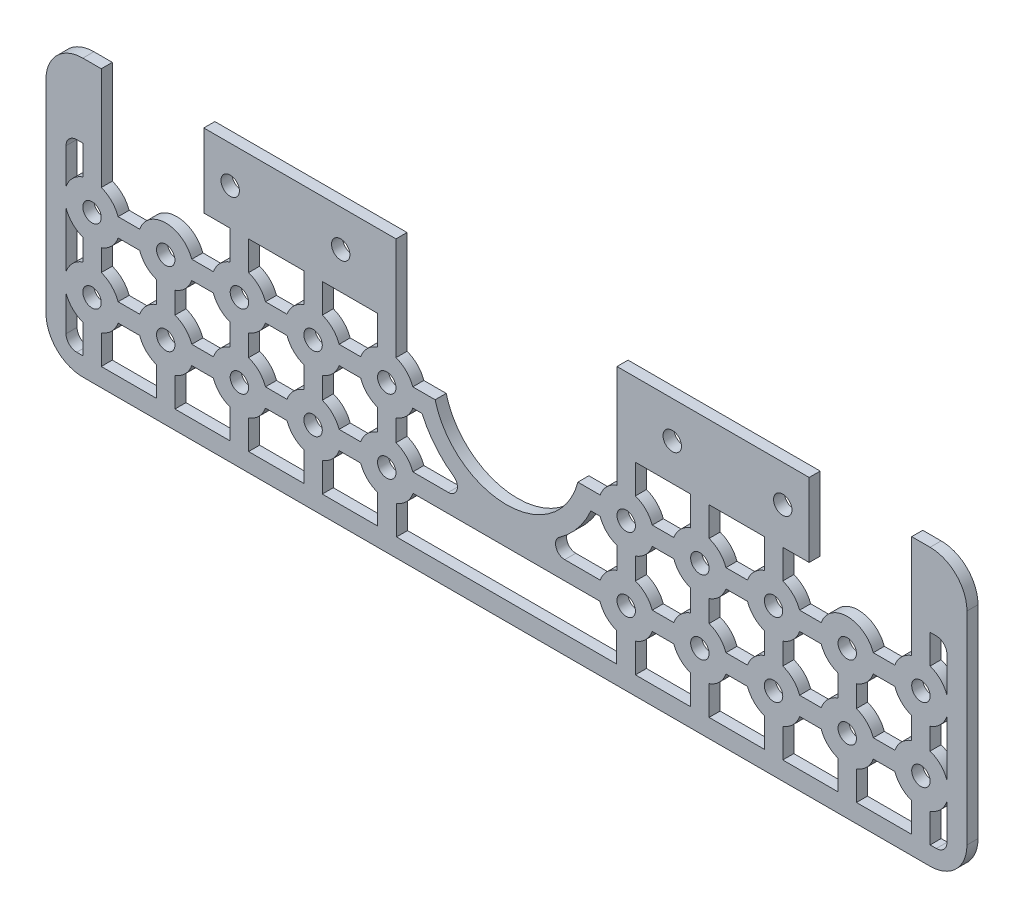
SolidWorks part; units mm, degrees
ref_plane "Front Plane" through (0, 0, 0) normal (0, 0, 1) x (1, 0, 0)
ref_plane "Top Plane" through (0, 0, 0) normal (0, 1, 0) x (1, 0, 0)
ref_plane "Right Plane" through (0, 0, 0) normal (1, 0, 0) x (0, 0, -1)
sketch "Sketch1" plane through (0, 0, 0) normal (0, 0, 1) x (1, 0, 0)
  line L0 (-40, 20) -> (-40, 55) construction
  line L4 (-250, -55) -> (-250, 55)
  line L5 (-239.1421, 10) -> (-239.1421, 29.2093)
  line L6 (-233.3514, 35) -> (-230, 35)
  line L8 (-60, 75) -> (-230, 75) construction
  line L17 (0, -20) -> (0, -40)
  line L21 (-239.1421, 0) -> (-239.1421, -30)
  line L25 (0, -65) -> (0, -75)
  line L26 (0, 75) -> (0, -75) construction
  line L27 (-50, 95) -> (50, 95) construction
  line L32 (-239.1421, -40) -> (-239.1421, -59.1675)
  line L34 (0, -75) -> (-230, -75)
  line L35 (-59.6991, -49.1887) -> (-59.6991, -65)
  line L77 (-230, 19.1421) -> (-230, 35)
  line L78 (-220, 19.1421) -> (-220, 35) construction
  line L79 (-230, -9.1421) -> (-230, -20.8579)
  line L80 (-220, -9.1421) -> (-220, -20.8579)
  line L81 (-220, -49.1421) -> (-220, -65)
  line L82 (-230, -49.1421) -> (-230, -64.9582)
  line L85 (-199.1421, 10) -> (-210.8579, 10)
  line L86 (-199.1421, 0) -> (-210.8579, 0)
  line L87 (-190, 19.1421) -> (-190, 35) construction
  line L88 (-180, 19.1421) -> (-180, 35) construction
  line L89 (-190, -9.1421) -> (-190, -20.8579)
  line L90 (-180, -9.1421) -> (-180, -20.8579)
  line L91 (-180, -49.1421) -> (-180, -65)
  line L92 (-190, -49.1421) -> (-190, -65)
  line L93 (-199.1421, -30) -> (-210.8579, -30)
  line L94 (-199.1421, -40) -> (-210.8579, -40)
  line L95 (-159.1421, 10) -> (-170.8579, 10)
  line L96 (-159.1421, 0) -> (-170.8579, 0)
  line L97 (-150, 19.1421) -> (-150, 35)
  line L98 (-140, 19.1421) -> (-140, 35)
  line L99 (-150, -9.1421) -> (-150, -20.8579)
  line L100 (-140, -9.1421) -> (-140, -20.8579)
  line L101 (-140, -49.1421) -> (-140, -65)
  line L102 (-150, -49.1421) -> (-150, -65)
  line L103 (-159.1421, -30) -> (-170.8579, -30)
  line L104 (-159.1421, -40) -> (-170.8579, -40)
  line L105 (-119.1421, 10) -> (-130.8579, 10)
  line L106 (-119.1421, 0) -> (-130.8579, 0)
  line L107 (-110, 19.1421) -> (-110, 35)
  line L108 (-100, 19.1421) -> (-100, 35)
  line L109 (-110, -9.1421) -> (-110, -20.8579)
  line L110 (-100, -9.1421) -> (-100, -20.8579)
  line L111 (-100, -49.1421) -> (-100, -65)
  line L112 (-110, -49.1421) -> (-110, -65)
  line L113 (-119.1421, -30) -> (-130.8579, -30)
  line L114 (-119.1421, -40) -> (-130.8579, -40)
  line L115 (-79.1421, 10) -> (-90.8579, 10)
  line L116 (-79.1421, 0) -> (-90.8579, 0)
  line L117 (-70, 19.1421) -> (-70, 35)
  line L118 (-59.6991, -65) -> (0, -65)
  line L119 (-70, -9.1421) -> (-70, -20.8579)
  line L122 (-70, -49.1421) -> (-70, -65)
  line L123 (-79.1421, -30) -> (-90.8579, -30)
  line L124 (-79.1421, -40) -> (-90.8579, -40)
  line L133 (-220, -65) -> (-190, -65)
  line L134 (-220, 35) -> (-190, 35) construction
  line L135 (-180, -65) -> (-150, -65)
  line L136 (-180, 35) -> (-150, 35) construction
  line L137 (-140, -65) -> (-110, -65)
  line L138 (-140, 35) -> (-110, 35)
  line L139 (-100, -65) -> (-70, -65)
  line L140 (-100, 35) -> (-70, 35)
  line L141 (0, -40) -> (-50.7025, -40)
  line L142 (-60, 19.1421) -> (-60, 35)
  line L143 (-60, -9.1421) -> (-60, -20.8579)
  line L147 (-50.8579, -30) -> (-31.6228, -30)
  line L149 (-50.8579, 0) -> (-45.8258, 0)
  line L150 (-50.8579, 10) -> (-48.9898, 10)
  line L154 (-233.3514, -64.9582) -> (-230, -64.9582)
  line L156 (-60, 75) -> (-230, 75) construction
  line L157 (-60, 75) -> (-60, 35)
  line L159 (-48.9898, 10) -> (-38.7298, 10)
  line L160 (-164.3309, 75) -> (-164.3309, 35)
  line L162 (-180, 35) -> (-190, 35) construction
  line L165 (-164.3309, 75) -> (-60, 75)
  line L167 (-230, 75) -> (-220, 75)
  line L169 (-164.3309, 35) -> (-150, 35)
  line L170 (-220, 19.1421) -> (-220, 75)
  arc A0 (-40, 20) -> (0, -20) centre (0, 20) ccw construction
  circle A1 centre (0, 20) radius 30 construction
  arc A4 (-230, -75) -> (-250, -55) centre (-230, -55) cw
  arc A5 (-250, 55) -> (-230, 75) centre (-230, 55) cw
  arc A7 (-40, 55) -> (-60, 75) centre (-60, 55) ccw construction
  arc A15 (-59.6991, -49.1887) -> (-50.7025, -40) centre (-65, -35) ccw
  arc A16 (-50.8579, 10) -> (-60, 19.1421) centre (-65, 5) ccw
  arc A17 (-60, -9.1421) -> (-50.8579, 0) centre (-65, 5) ccw
  arc A22 (-60, -20.8579) -> (-50.8579, -30) centre (-65, -35) cw
  arc A23 (-28.748, -20.9091) -> (-45.8258, 0) centre (0, 20) cw
  circle A26 centre (-150, 55) radius 5
  circle A27 centre (-90, 55) radius 5
  arc A43 (-31.6228, -30) -> (-28.748, -20.9091) centre (-31.6228, -25) ccw
  arc A64 (-230, 19.1421) -> (-239.1421, 10) centre (-225, 5) ccw
  arc A65 (-210.8579, 10) -> (-220, 19.1421) centre (-225, 5) ccw
  arc A66 (-220, -9.1421) -> (-210.8579, 0) centre (-225, 5) ccw
  arc A67 (-239.1421, 0) -> (-230, -9.1421) centre (-225, 5) ccw
  arc A68 (-220, -20.8579) -> (-210.8579, -30) centre (-225, -35) cw
  arc A69 (-210.8579, -40) -> (-220, -49.1421) centre (-225, -35) cw
  arc A70 (-230, -49.1421) -> (-239.1421, -40) centre (-225, -35) cw
  arc A71 (-239.1421, -30) -> (-230, -20.8579) centre (-225, -35) cw
  arc A72 (-190, 19.1421) -> (-199.1421, 10) centre (-185, 5) ccw
  arc A73 (-170.8579, 10) -> (-180, 19.1421) centre (-185, 5) ccw
  arc A74 (-180, -9.1421) -> (-170.8579, 0) centre (-185, 5) ccw
  arc A75 (-199.1421, 0) -> (-190, -9.1421) centre (-185, 5) ccw
  arc A76 (-180, -20.8579) -> (-170.8579, -30) centre (-185, -35) cw
  arc A77 (-170.8579, -40) -> (-180, -49.1421) centre (-185, -35) cw
  arc A78 (-190, -49.1421) -> (-199.1421, -40) centre (-185, -35) cw
  arc A79 (-199.1421, -30) -> (-190, -20.8579) centre (-185, -35) cw
  arc A80 (-150, 19.1421) -> (-159.1421, 10) centre (-145, 5) ccw
  arc A81 (-130.8579, 10) -> (-140, 19.1421) centre (-145, 5) ccw
  arc A82 (-140, -9.1421) -> (-130.8579, 0) centre (-145, 5) ccw
  arc A83 (-159.1421, 0) -> (-150, -9.1421) centre (-145, 5) ccw
  arc A84 (-140, -20.8579) -> (-130.8579, -30) centre (-145, -35) cw
  arc A85 (-130.8579, -40) -> (-140, -49.1421) centre (-145, -35) cw
  arc A86 (-150, -49.1421) -> (-159.1421, -40) centre (-145, -35) cw
  arc A87 (-159.1421, -30) -> (-150, -20.8579) centre (-145, -35) cw
  arc A88 (-110, 19.1421) -> (-119.1421, 10) centre (-105, 5) ccw
  arc A89 (-90.8579, 10) -> (-100, 19.1421) centre (-105, 5) ccw
  arc A90 (-100, -9.1421) -> (-90.8579, 0) centre (-105, 5) ccw
  arc A91 (-119.1421, 0) -> (-110, -9.1421) centre (-105, 5) ccw
  arc A92 (-100, -20.8579) -> (-90.8579, -30) centre (-105, -35) cw
  arc A93 (-90.8579, -40) -> (-100, -49.1421) centre (-105, -35) cw
  arc A94 (-110, -49.1421) -> (-119.1421, -40) centre (-105, -35) cw
  arc A95 (-119.1421, -30) -> (-110, -20.8579) centre (-105, -35) cw
  arc A96 (-70, 19.1421) -> (-79.1421, 10) centre (-65, 5) ccw
  arc A97 (-233.3514, -64.9582) -> (-239.1421, -59.1675) centre (-233.3514, -59.1675) cw
  arc A99 (-79.1421, 0) -> (-70, -9.1421) centre (-65, 5) ccw
  arc A102 (-70, -49.1421) -> (-79.1421, -40) centre (-65, -35) cw
  arc A103 (-79.1421, -30) -> (-70, -20.8579) centre (-65, -35) cw
  circle A111 centre (-225, 5) radius 5
  circle A112 centre (-225, -35) radius 5
  circle A113 centre (-185, 5) radius 5
  circle A114 centre (-185, -35) radius 5
  circle A115 centre (-145, 5) radius 5
  circle A116 centre (-145, -35) radius 5
  circle A117 centre (-105, 5) radius 5
  circle A118 centre (-105, -35) radius 5
  circle A119 centre (-65, 5) radius 5
  circle A120 centre (-65, -35) radius 5
  arc A123 (-233.3514, 35) -> (-239.1421, 29.2093) centre (-233.3514, 29.2093) ccw
  arc A124 (0, -20) -> (-38.7298, 10) centre (0, 20) cw
  arc A125 (-190, 19.1421) -> (-180, 19.1421) centre (-185, 5) cw
  point P0 (0, 0)
  point P11 (0, 50)
  point P30 (-40, 75)
  point P45 (0, -30)
  point P74 (0, 95)
  dimension "D3" = 80
  dimension "D4" = 60
  dimension "D6" = 55
  dimension "D7" = 75
  dimension "D10" = 75
  dimension "D11" = 20
  dimension "D12" = 5.7907
  dimension "D15" = 75
  dimension "D20" = 10
  dimension "D21" = 10
  dimension "D25" = 5
  dimension "D8" = 20
  dimension "D5" = 2
  dimension "D9" = 20
  dimension "D13" = 210
  dimension "D16" = 100
  dimension "D17" = 20
  dimension "D19" = 20
  dimension "D22" = 20
  dimension "D23" = 100
  dimension "D24" = 50
  dimension "D26" = 250
extrude "Boss-Extrude1" add sketch "Sketch1" along normal blind 6
mirror "Mirror1" about plane through (0, -20, 6) normal (-1, 0, 0) of "Boss-Extrude1"
